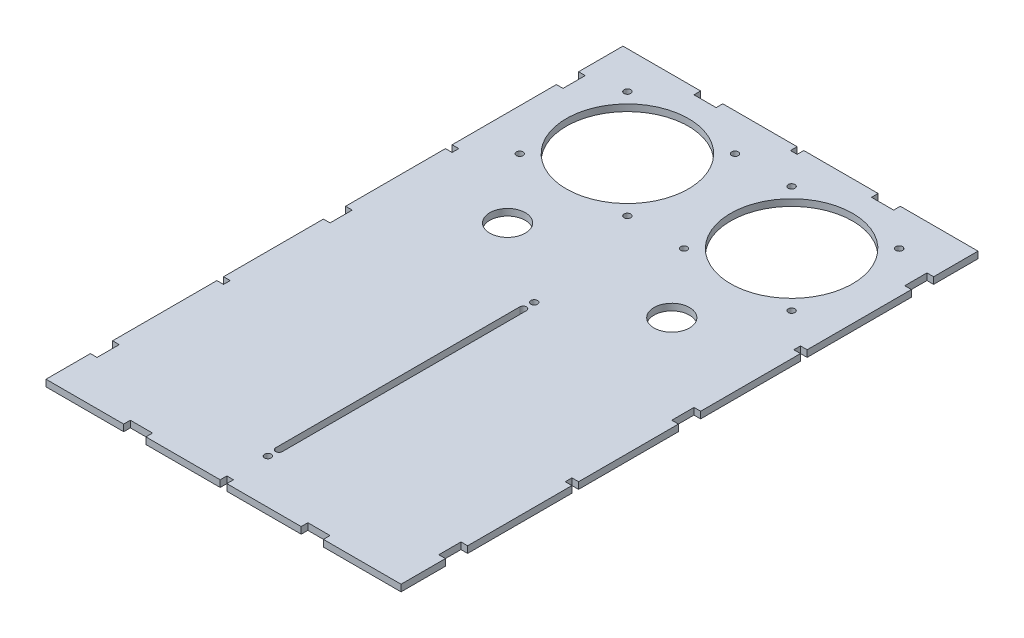
SolidWorks part; units mm, degrees
ref_plane "Front Plane" through (0, 0, 0) normal (0, 0, 1) x (1, 0, 0)
ref_plane "Top Plane" through (0, 0, 0) normal (0, 1, 0) x (1, 0, 0)
ref_plane "Right Plane" through (0, 0, 0) normal (1, 0, 0) x (0, 0, -1)
sketch "Sketch1" plane through (0, 0, 0) normal (0, 1, 0) x (1, 0, 0)
  line L1 (-80, 110) -> (80, 110)
  line L2 (-80, 110) -> (-80, -150)
  line L3 (-80, -150) -> (80, -150)
  line L4 (80, 110) -> (80, -150)
  dimension "D1" = 160
  dimension "D2" = 150
  dimension "D3" = 80
  dimension "D4" = 110
extrude "Boss-Extrude1" add sketch "Sketch1" along normal blind 3
sketch "Sketch2" plane through (0, 3, 0) normal (0, 1, 0) x (1, 0, 0)
  line L0 (0, 160.4119) -> (0, -162.8836) construction
  line L1 (90.0224, 69) -> (-93.0511, 69) construction
  line L2 (-37, 122.7504) -> (-37, 0) construction
  line L3 (0, -15) -> (0, -125) construction
  line L4 (1.5, -15) -> (1.5, -125)
  line L5 (-1.5, -15) -> (-1.5, -125)
  line L6 (104.7892, 0) -> (-107.8107, 0) construction
  circle A0 centre (0, -10) radius 1.5
  arc A1 (1.5, -15) -> (-1.5, -15) centre (0, -15) ccw
  arc A2 (-1.5, -125) -> (1.5, -125) centre (0, -125) ccw
  circle A3 centre (0, -130) radius 1.5
  circle A4 centre (-37, 15) radius 8
  circle A5 centre (-12.75, 93.25) radius 1.5
  circle A6 centre (37, 15) radius 8
  circle A7 centre (-12.75, 44.75) radius 1.5
  circle A8 centre (-61.25, 44.75) radius 1.5
  circle A9 centre (-61.25, 93.25) radius 1.5
  circle A10 centre (37, 69) radius 27.5
  circle A11 centre (12.75, 44.75) radius 1.5
  circle A12 centre (61.25, 44.75) radius 1.5
  circle A13 centre (61.25, 93.25) radius 1.5
  circle A14 centre (-37, 69) radius 27.5
  circle A15 centre (12.75, 93.25) radius 1.5
  point P11 (0, -70)
  point P33 (-37, 69)
  point P53 (-35, 69)
  dimension "D1" = 3
  dimension "D4" = 3
  dimension "D8" = 16
  dimension "D9" = 24.25
  dimension "D24" = 3
  dimension "D19" = 55
  dimension "D12" = 4
  dimension "D2" = 3
  dimension "D3" = 5
  dimension "D5" = 120
  dimension "D6" = 5
  dimension "D7" = 10
  dimension "D11" = 15
  dimension "D13" = 37
  dimension "D16" = 24.25
  dimension "D27" = 69
extrude "Cut-Extrude1" cut sketch "Sketch2" against normal blind 3
sketch "Sketch7" plane through (0, 3, 0) normal (0, 1, 0) x (1, 0, 0)
  line L0 (80, 110) -> (-80, 110) construction
  line L1 (1.5, 107) -> (-1.5, 107)
  line L2 (1.5, 107) -> (1.5, 110)
  line L3 (1.5, 110) -> (-1.5, 110)
  line L4 (-1.5, 107) -> (-1.5, 110)
  line L5 (0, 122.6308) -> (0, 84.273) construction
  line L6 (45, 107) -> (45, 110)
  line L7 (-35, 107) -> (-45, 107)
  line L8 (-35, 107) -> (-35, 110)
  line L9 (-35, 110) -> (-45, 110)
  line L10 (-45, 107) -> (-45, 110)
  line L11 (35, 110) -> (45, 110)
  line L12 (35, 107) -> (35, 110)
  line L13 (35, 107) -> (45, 107)
  line L14 (-80, -20) -> (80, -20) construction
  line L15 (-80, 110) -> (-80, -150) construction
  line L16 (80, -150) -> (80, 110) construction
  line L17 (35, -147) -> (45, -147)
  line L18 (35, -147) -> (35, -150)
  line L19 (35, -150) -> (45, -150)
  line L20 (-45, -147) -> (-45, -150)
  line L21 (-35, -150) -> (-45, -150)
  line L22 (-35, -147) -> (-35, -150)
  line L23 (-35, -147) -> (-45, -147)
  line L24 (45, -147) -> (45, -150)
  line L25 (-1.5, -147) -> (-1.5, -150)
  line L26 (1.5, -150) -> (-1.5, -150)
  line L27 (1.5, -147) -> (1.5, -150)
  line L28 (1.5, -147) -> (-1.5, -147)
  line L29 (-77, -130) -> (-77, -120)
  line L30 (-80, -15) -> (-77, -15)
  line L31 (-80, -15) -> (-80, -25)
  line L32 (-80, -25) -> (-77, -25)
  line L33 (-77, -15) -> (-77, -25)
  line L34 (-80, 90) -> (-77, 90)
  line L35 (-80, 90) -> (-80, 80)
  line L36 (-80, 80) -> (-77, 80)
  line L37 (-77, 90) -> (-77, 80)
  line L38 (-80, -120) -> (-77, -120)
  line L39 (-80, -130) -> (-80, -120)
  line L40 (-80, -130) -> (-77, -130)
  line L41 (-77, -73) -> (-77, -70)
  line L42 (-80, 33) -> (-77, 33)
  line L43 (-80, 33) -> (-80, 30)
  line L44 (-80, 30) -> (-77, 30)
  line L45 (-77, 33) -> (-77, 30)
  line L46 (-80, -70) -> (-77, -70)
  line L47 (-80, -73) -> (-80, -70)
  line L48 (-80, -73) -> (-77, -73)
  line L49 (80, -130) -> (77, -130)
  line L50 (80, -130) -> (80, -120)
  line L51 (80, -120) -> (77, -120)
  line L52 (77, -130) -> (77, -120)
  line L53 (80, -73) -> (77, -73)
  line L54 (80, -73) -> (80, -70)
  line L55 (80, -70) -> (77, -70)
  line L56 (77, -73) -> (77, -70)
  line L57 (77, -15) -> (77, -25)
  line L58 (80, -25) -> (77, -25)
  line L59 (80, -15) -> (80, -25)
  line L60 (80, -15) -> (77, -15)
  line L61 (77, 33) -> (77, 30)
  line L62 (80, 30) -> (77, 30)
  line L63 (80, 33) -> (80, 30)
  line L64 (80, 33) -> (77, 33)
  line L65 (77, 90) -> (77, 80)
  line L66 (80, 80) -> (77, 80)
  line L67 (80, 90) -> (80, 80)
  line L68 (80, 90) -> (77, 90)
  dimension "D1" = 3
  dimension "D2" = 3
  dimension "D3" = 1.5
  dimension "D4" = 10
  dimension "D5" = 3
  dimension "D6" = 45
  dimension "D7" = 5
  dimension "D8" = 10
  dimension "D9" = 3
  dimension "D10" = 3
  dimension "D11" = 10
  dimension "D12" = 100
  dimension "D13" = 3
  dimension "D14" = 3
  dimension "D15" = 50
extrude "Cut-Extrude2" cut sketch "Sketch7" against normal through all
